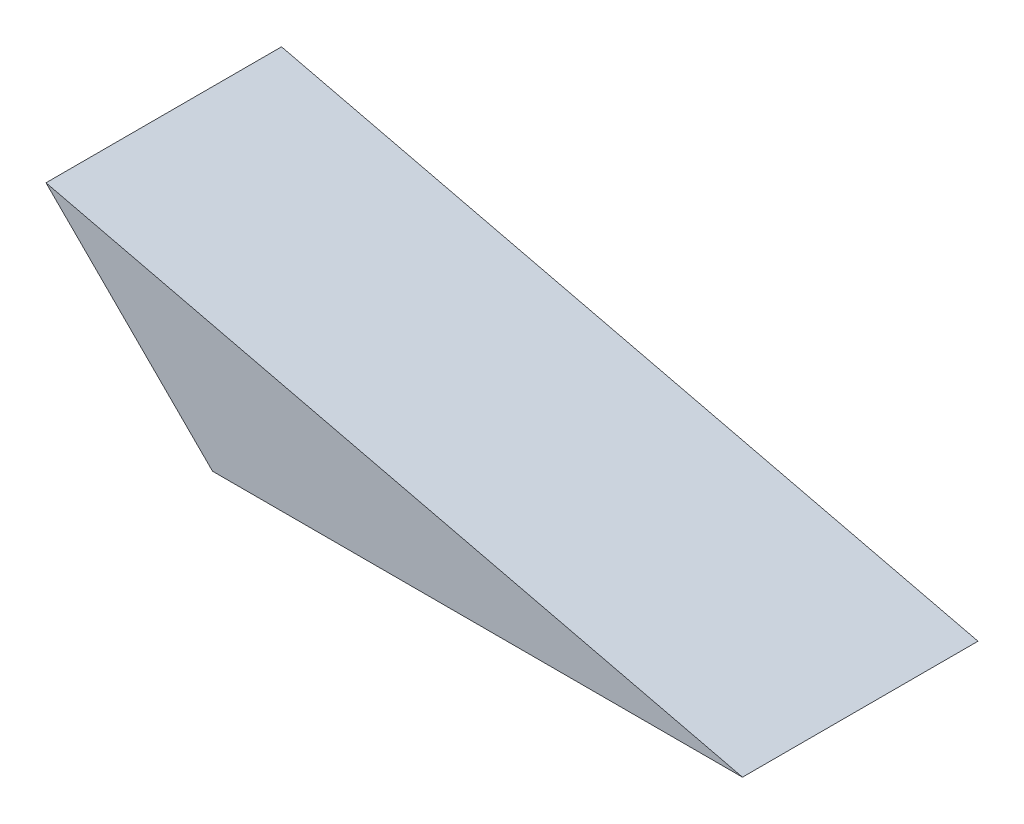
SolidWorks part; units mm, degrees
material "1023 Carbon Steel Sheet (SS)"
ref_plane "Front Plane" through (0, 0, 0) normal (0, 0, 1) x (1, 0, 0)
ref_plane "Top Plane" through (0, 0, 0) normal (0, 1, 0) x (1, 0, 0)
ref_plane "Right Plane" through (0, 0, 0) normal (1, 0, 0) x (0, 0, -1)
sketch "Sketch1" plane through (0, 0, 0) normal (0, 0, 1) x (1, 0, 0)
  line L0 (0, 0) -> (9, 0)
  line L1 (9, 0) -> (-2.8284, 2.8284)
  line L2 (-2.8284, 2.8284) -> (0, 0)
  dimension "D1" = 9
  dimension "D2" = 4
  dimension "D3" = 135
extrude "Boss-Extrude1" add sketch "Sketch1" along normal blind 4
